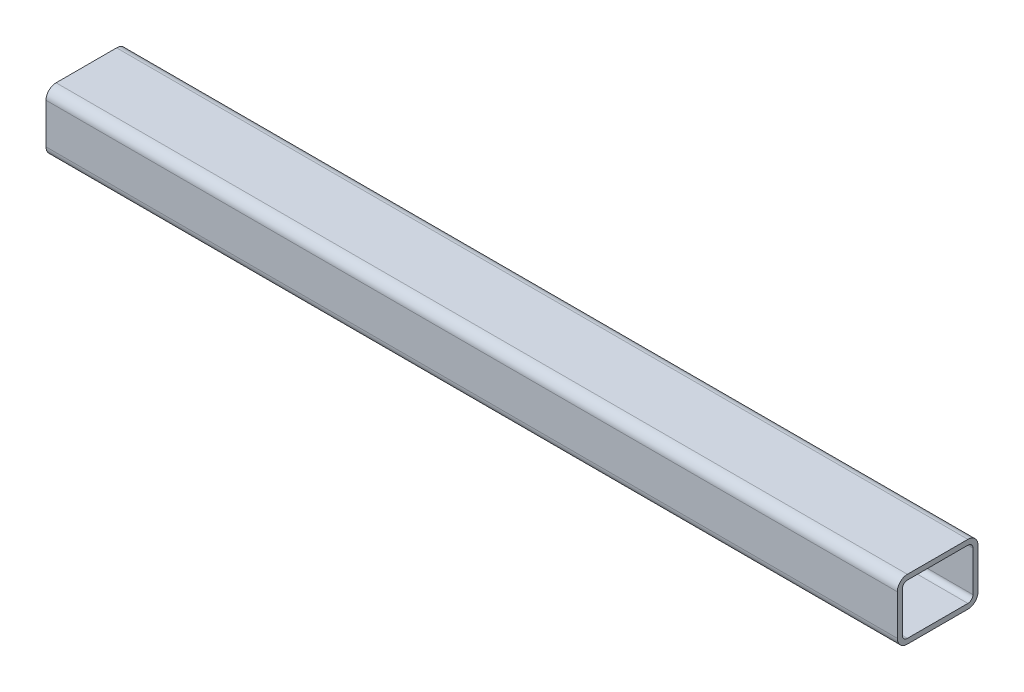
SolidWorks part; units mm, degrees
material "Q235"
ref_plane "前视基准面" through (0, 0, 0) normal (0, 0, 1) x (1, 0, 0)
ref_plane "上视基准面" through (0, 0, 0) normal (0, 1, 0) x (1, 0, 0)
ref_plane "右视基准面" through (0, 0, 0) normal (1, 0, 0) x (0, 0, -1)
sketch "尺寸草图" plane through (0, 0, 0) normal (1, 0, 0) x (0, 0, -1)
  line L0 (-25.8313, 0) -> (35, 0) construction
  line L1 (0, 56.0755) -> (0, -63.3818) construction
  line L2 (-30, 25) -> (30, 25)
  line L3 (-30, 30) -> (30, 30)
  line L4 (-40, 20) -> (-40, -20)
  line L5 (-30, -30) -> (30, -30)
  line L6 (40, 20) -> (40, -20)
  line L7 (35, 20) -> (35, -20)
  line L8 (-30, -25) -> (30, -25)
  line L9 (-35, 20) -> (-35, -20)
  line L10 (-40, 30) -> (-40, -30) construction
  line L11 (-40, -30) -> (40, -30) construction
  line L12 (-35, -25) -> (35, -25) construction
  line L13 (-35, 25) -> (-35, -25) construction
  line L14 (35, 25) -> (35, -25) construction
  line L15 (40, 30) -> (40, -30) construction
  line L16 (-35, 25) -> (35, 25) construction
  line L17 (-40, 30) -> (40, 30) construction
  arc A0 (-40, -20) -> (-30, -30) centre (-30, -20) ccw
  arc A1 (-30, -25) -> (-35, -20) centre (-30, -20) cw
  arc A2 (35, -20) -> (30, -25) centre (30, -20) cw
  arc A3 (30, -30) -> (40, -20) centre (30, -20) ccw
  arc A4 (30, 25) -> (35, 20) centre (30, 20) cw
  arc A5 (30, 30) -> (40, 20) centre (30, 20) cw
  arc A6 (-30, 25) -> (-35, 20) centre (-30, 20) ccw
  arc A7 (-30, 30) -> (-40, 20) centre (-30, 20) ccw
  dimension "D2" = 10
  dimension "H" = 60
  dimension "B" = 80
  dimension "t" = 5
extrude "凸台-拉伸1" add sketch "尺寸草图" along normal mid plane 844
